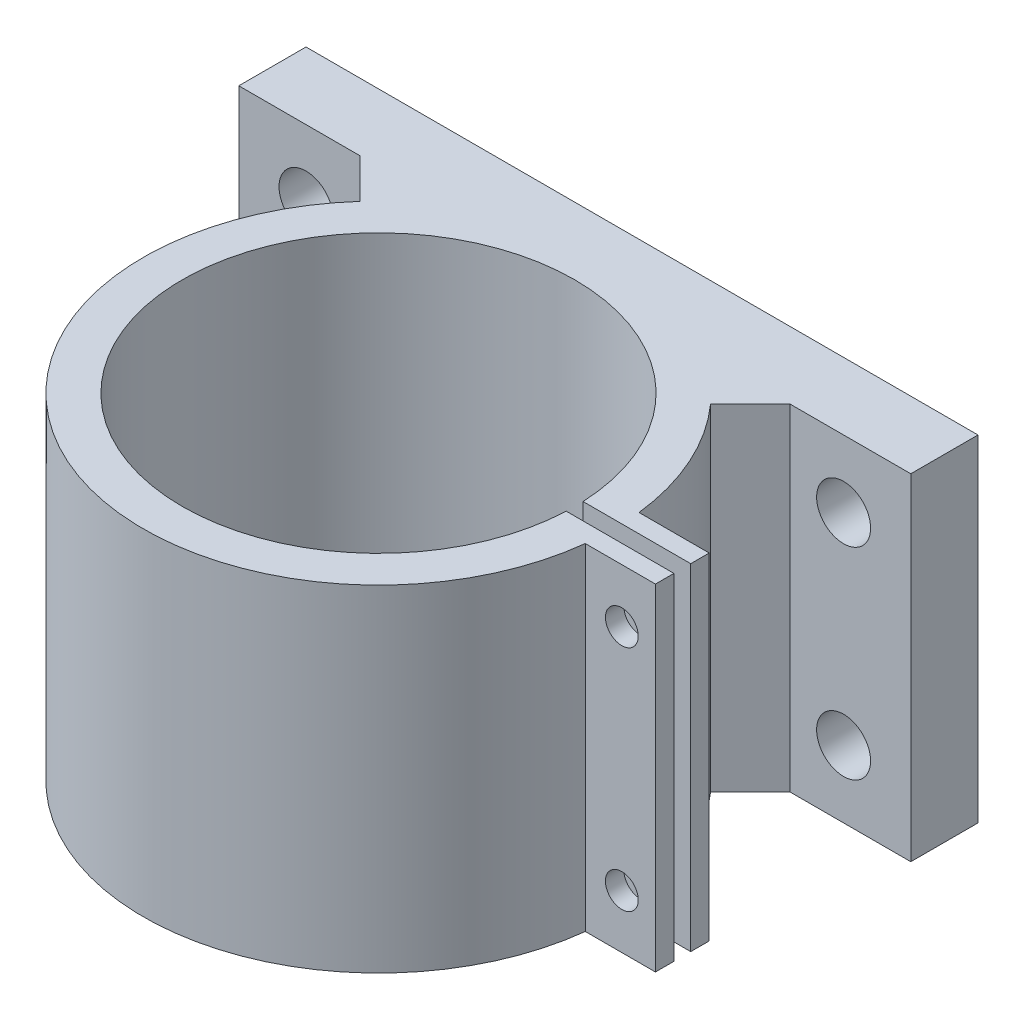
SolidWorks part; units mm, degrees
ref_plane "Front Plane" through (0, 0, 0) normal (0, 0, 1) x (1, 0, 0)
ref_plane "Top Plane" through (0, 0, 0) normal (0, 1, 0) x (1, 0, 0)
ref_plane "Right Plane" through (0, 0, 0) normal (1, 0, 0) x (0, 0, -1)
sketch "Sketch1" plane through (0, 0, 0) normal (0, 1, 0) x (1, 0, 0)
  line L0 (0, 18.55) -> (-31.75, 18.55)
  line L5 (-31.75, 18.55) -> (-31.75, 24.9)
  line L6 (0, 18.55) -> (31.75, 18.55)
  line L7 (-31.75, 24.9) -> (31.75, 24.9)
  line L8 (64.3078, 22.225) -> (-54.8198, 22.225) construction
  line L9 (64.3078, 18.55) -> (-54.8198, 18.55) construction
  line L10 (-28.575, 15.0158) -> (-23.575, 15.0158)
  line L11 (-28.575, 15.0158) -> (-28.575, 41.4443)
  line L12 (-28.575, 41.4443) -> (-23.575, 41.4443)
  line L13 (-23.575, 15.0158) -> (-23.575, 41.4443)
  line L14 (-28.575, 15.0158) -> (-23.575, 41.4443) construction
  line L15 (-28.575, 41.4443) -> (-23.575, 15.0158) construction
  line L16 (31.75, 24.9) -> (31.75, 18.55)
  line L17 (-40.3092, 0) -> (51.164, 0) construction
  line L18 (18.55, 0) -> (18.55, -2.54)
  line L19 (18.55, -2.54) -> (28.71, -2.54)
  line L20 (18.55, 0) -> (18.55, 2.54)
  line L21 (18.55, 2.54) -> (28.71, 2.54)
  line L22 (28.71, 2.54) -> (28.71, -2.54)
  line L23 (20.32, 18.55) -> (16.5755, 14.8055)
  line L24 (23.7993, 5.7462) -> (26.7993, 5.7462)
  line L25 (23.7993, 5.7462) -> (23.7993, -10.3543)
  line L26 (23.7993, -10.3543) -> (26.7993, -10.3543)
  line L27 (26.7993, 5.7462) -> (26.7993, -10.3543)
  line L28 (-20.32, 18.55) -> (-16.5755, 14.8055)
  circle A0 centre (0, 0) radius 18.55
  circle A1 centre (0, 0) radius 22.225
  point P5 (-26.075, 28.2301)
  dimension "D1" = 37.1
  dimension "D2" = 44.45
  dimension "D3" = 31.75
  dimension "D4" = 6.35
  dimension "D5" = 5
  dimension "D6" = 31.75
  dimension "D7" = 3.175
  dimension "D8" = 2.54
  dimension "D9" = 10.16
  dimension "D10" = 2.54
  dimension "D11" = 3
  dimension "D12" = 11.43
  dimension "D13" = 45
  dimension "D14" = 45
  dimension "D15" = 11.43
extrude "Boss-Extrude1" add sketch "Sketch1" along normal blind 31.75 contours L0 A1 L19 L18 A0 | L21 A1 L6 A0 L20 | L19 A1 L21 L20 L18 | A1 L19 L25 L21 | L27 L21 L25 L19 | L21 L27 L19 L22 | A1 L6 L16 L7 L13 L0 | L6 A1 L0 | A1 L23 L6 | A1 L0 L28 | L0 L13 L7 L11 | L0 L11 L7 L5
sketch "Sketch2" plane through (0, 31.75, 0) normal (0, 1, 0) x (1, 0, 0)
  line L0 (0, 0) -> (49.7855, 0) construction
  line L2 (11.3208, -0.7937) -> (32.7332, -0.7937)
  line L3 (11.3208, -0.7937) -> (11.3208, 0.7938)
  line L4 (11.3208, 0.7938) -> (32.7332, 0.7938)
  line L5 (32.7332, -0.7937) -> (32.7332, 0.7938)
  line L6 (11.3208, -0.7937) -> (32.7332, 0.7938) construction
  line L7 (11.3208, 0.7938) -> (32.7332, -0.7937) construction
  point P3 (22.027, 0)
  dimension "D1" = 1.5875
extrude "Cut-Extrude1" cut sketch "Sketch2" against normal blind 31.75
sketch "Sketch3" plane through (0, 0, 2.54) normal (0, 0, 1) x (1, 0, 0)
  line L0 (28.71, 31.75) -> (28.71, 0) construction
  line L1 (22.0794, 0) -> (28.71, 0) construction
  line L2 (22.0794, 31.75) -> (28.71, 31.75) construction
  circle A0 centre (25.535, 5.08) radius 1.55
  circle A1 centre (25.535, 26.67) radius 1.55
  dimension "D1" = 3.1
  dimension "D4" = 3.1
  dimension "D2" = 3.175
  dimension "D3" = 5.08
  dimension "D5" = 3.175
  dimension "D6" = 5.08
extrude "Cut-Extrude2" cut sketch "Sketch3" against normal up to surface (5.08 mm away) up to face at (25.3947, 15.875, -2.54)
sketch "Sketch4" plane through (0, 0, -18.55) normal (0, 0, 1) x (1, 0, 0)
  line L0 (-31.75, 31.75) -> (-31.75, 0) construction
  line L1 (-20.32, 0) -> (-31.75, 0) construction
  line L2 (-20.32, 31.75) -> (-31.75, 31.75) construction
  circle A0 centre (-25.4, 6.35) radius 2.55
  circle A1 centre (-25.4, 25.4) radius 2.55
  circle A2 centre (25.4, 25.4) radius 2.55
  circle A3 centre (25.4, 6.35) radius 2.55
  dimension "D1" = 5.1
  dimension "D2" = 5.1
  dimension "D3" = 5.1
  dimension "D4" = 5.1
  dimension "D5" = 50.8
  dimension "D6" = 6.35
  dimension "D7" = 6.35
  dimension "D8" = 0
  dimension "D9" = 50.8
  dimension "D10" = 6.35
  dimension "D11" = 0
  dimension "D12" = 6.35
extrude "Cut-Extrude3" cut sketch "Sketch4" against normal blind 31.75
equation "\"5mm.\"=0.201728"
